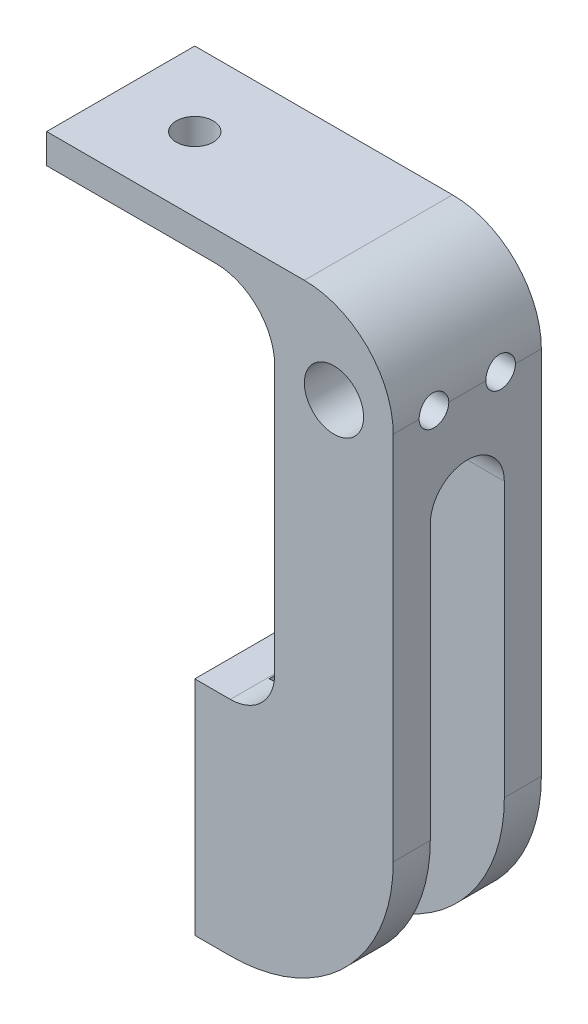
SolidWorks part; units mm, degrees
ref_plane "Front Plane" through (0, 0, 0) normal (0, 0, 1) x (1, 0, 0)
ref_plane "Top Plane" through (0, 0, 0) normal (0, 1, 0) x (1, 0, 0)
ref_plane "Right Plane" through (0, 0, 0) normal (1, 0, 0) x (0, 0, -1)
sketch "Sketch1" plane through (0, 0, 0) normal (0, 0, 1) x (1, 0, 0)
  line L0 (-10, -20) -> (-10, -40) construction
  line L1 (10, -20) -> (-10, -20) construction
  line L2 (10, -20) -> (10, 20) construction
  line L3 (10, 20) -> (-10, 20) construction
  line L4 (-10, -20) -> (-10, 20) construction
  line L5 (10, -20) -> (-10, 20) construction
  line L6 (10, 20) -> (-10, -20) construction
  line L7 (-50, 0) -> (-10, 0) construction
  line L8 (-50, 0) -> (-50, -20) construction
  line L9 (-50, -20) -> (-10, -20) construction
  line L10 (-10, 0) -> (-10, -20) construction
  line L11 (-50, 0) -> (-10, -20) construction
  line L12 (-50, -20) -> (-10, 0) construction
  line L13 (-10, -40) -> (10, -40) construction
  line L14 (10, -40) -> (10, -20) construction
  line L15 (-10, 20) -> (-10, 25) construction
  line L16 (-10, 25) -> (10, 25) construction
  line L17 (10, 25) -> (10, 20) construction
  line L19 (-10, 25) -> (12.8, 25)
  line L20 (-10, 25) -> (-10, 29)
  line L21 (-10, 29) -> (24.8, 29)
  line L23 (-10, -25) -> (14.8, -25)
  line L24 (-10, -25) -> (-10, -55)
  line L25 (-10, -55) -> (14.8, -55)
  line L27 (36.8, 17) -> (36.8, -33)
  line L28 (20.8, 17) -> (20.8, -19)
  circle A0 centre (28.8, 17) radius 4
  circle A1 centre (28.8, 17) radius 8 construction
  arc A2 (24.8, 29) -> (36.8, 17) centre (24.8, 17) cw
  arc A3 (36.8, -33) -> (14.8, -55) centre (14.8, -33) cw
  arc A4 (12.8, 25) -> (20.8, 17) centre (12.8, 17) cw
  arc A5 (20.8, -19) -> (14.8, -25) centre (14.8, -19) cw
  circle A6 centre (0, -35) radius 2
  point P0 (0, 0)
  point P6 (-30, -10)
  dimension "D10" = 8
  dimension "D14" = 6
  dimension "D15" = 22
  dimension "D16" = 4
  dimension "D17" = 10
  dimension "D18" = 10
  dimension "D1" = 20
  dimension "D2" = 40
  dimension "D3" = 20
  dimension "D4" = 40
  dimension "D5" = 20
  dimension "D6" = 5
  dimension "D7" = 4
  dimension "D8" = 30
  dimension "D9" = 50
  dimension "D11" = 26.8
  dimension "D12" = 16
  dimension "D13" = 12
  dimension "D19" = 18.8
  dimension "D20" = 17
extrude "Boss-Extrude1" add sketch "Sketch1" along normal blind 25
sketch "Sketch2" plane through (0, -25, 0) normal (0, 1, 0) x (1, 0, 0)
  line L1 (-10, 0) -> (10, 0)
  line L2 (-10, 0) -> (-10, -20)
  line L3 (-10, -20) -> (10, -20)
  line L4 (10, 0) -> (10, -20)
  dimension "D1" = 20
  dimension "D2" = 20
extrude "Cut-Extrude1" cut sketch "Sketch2" against normal blind 30
sketch "Sketch3" plane through (0, 29, 0) normal (0, 1, 0) x (1, 0, 0)
  line L1 (10, -20) -> (-10, -20) construction
  line L2 (10, -20) -> (10, 0) construction
  line L3 (10, 0) -> (-10, 0) construction
  line L4 (-10, -20) -> (-10, 0) construction
  line L5 (10, -20) -> (-10, 0) construction
  line L6 (10, 0) -> (-10, -20) construction
  circle A0 centre (0, -10) radius 2.5
  point P0 (0, -10)
  dimension "D3" = 5
  dimension "D1" = 20
  dimension "D2" = 20
extrude "Cut-Extrude2" cut sketch "Sketch3" against normal blind 25
sketch "Sketch6" plane through (0, 0, 25) normal (0, 0, 1) x (1, 0, 0)
  line L1 (-50, -75) -> (50, -75)
  line L2 (-50, -75) -> (-50, 75)
  line L3 (-50, 75) -> (50, 75)
  line L4 (50, -75) -> (50, 75)
  line L5 (-50, -75) -> (50, 75) construction
  line L6 (-50, 75) -> (50, -75) construction
  point P0 (0, 0)
  dimension "D1" = 100
  dimension "D2" = 150
extrude "Cut-Extrude5" cut sketch "Sketch6" against normal blind 5
sketch "Sketch7" plane through (36.8, 0, 0) normal (1, 0, 0) x (0, 0, -1)
  line L0 (-20, 17) -> (0, 17) construction
  line L1 (-10, 4) -> (-10, -56) construction
  line L2 (-5, 4) -> (-5, -56)
  line L3 (-15, 4) -> (-15, -56)
  line L4 (-20, 29) -> (0, 29) construction
  line L5 (-20, 17) -> (-20, -33) construction
  line L6 (0, -33) -> (0, 17) construction
  arc A0 (-5, 4) -> (-15, 4) centre (-10, 4) ccw
  arc A1 (-15, -56) -> (-5, -56) centre (-10, -56) ccw
  point P6 (-10, -26)
  point P11 (-10, 9)
  dimension "D1" = 20
  dimension "D2" = 5
  dimension "D3" = 5
  dimension "D4" = 60
extrude "Cut-Extrude6" cut sketch "Sketch7" against normal blind 21.8
sketch "Sketch8" plane through (15, 0, 0) normal (1, 0, 0) x (0, 0, -1)
  line L1 (-10, -31.9967) -> (-15, -24.9967) construction
  line L2 (-5, -24.9967) -> (-15, -24.9967) construction
  line L3 (-10, -47.9991) -> (-15, -54.9991) construction
  line L5 (-10, -31.9967) -> (-10, -47.9991) construction
  circle A0 centre (-10, -31.9967) radius 2
  circle A1 centre (-10, -47.9991) radius 2
  point P11 (-10, -24.9967)
  dimension "D1" = 4
  dimension "D2" = 7
extrude "Cut-Extrude7" cut sketch "Sketch8" against normal blind 21.8
sketch "Sketch9" plane through (36.8, 0, 0) normal (1, 0, 0) x (0, 0, -1)
  line L0 (-20, 17) -> (0, 17) construction
  line L1 (-20, 17) -> (-20, -33) construction
  line L2 (0, -33) -> (0, 17) construction
  circle A0 centre (-14.5, 17) radius 2
  circle A1 centre (-5.5, 17) radius 2
  dimension "D1" = 5.5
  dimension "D2" = 5.5
  dimension "D3" = 4
  dimension "D4" = 4
extrude "Cut-Extrude8" cut sketch "Sketch9" against normal blind 6
